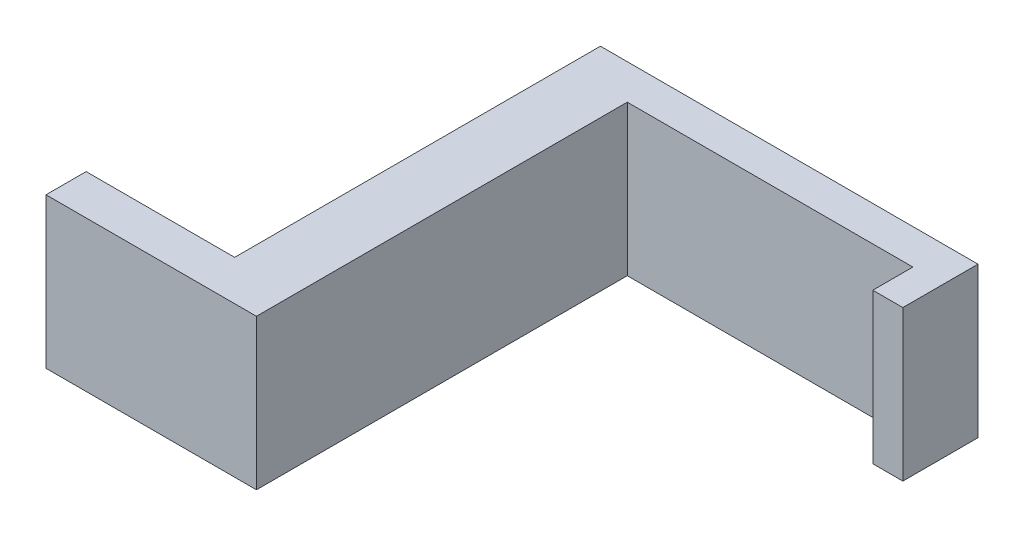
SolidWorks part; units mm, degrees
ref_plane "Front Plane" through (0, 0, 0) normal (0, 0, 1) x (1, 0, 0)
ref_plane "Top Plane" through (0, 0, 0) normal (0, 1, 0) x (1, 0, 0)
ref_plane "Right Plane" through (0, 0, 0) normal (1, 0, 0) x (0, 0, -1)
sketch "Sketch2" plane through (0, 0, 0) normal (0, 1, 0) x (1, 0, 0)
  line L0 (0, 0) -> (0, 22)
  line L1 (0, 22) -> (19, 22)
  line L2 (19, 22) -> (19, 19.3331)
  line L3 (19, 19.3331) -> (21, 19.3331)
  line L4 (21, 19.3331) -> (21, 24.3331)
  line L5 (21, 24.3331) -> (-4.1195, 24.3331)
  line L6 (-4.1195, 24.3331) -> (-4.1195, 0)
  line L7 (-4.1195, 0) -> (-14, 0)
  line L8 (-14, 0) -> (-14, -2.6706)
  line L9 (-14, -2.6706) -> (0, -2.6706)
  line L10 (0, -2.6706) -> (0, 0)
extrude "Boss-Extrude1" add sketch "Sketch2" along normal blind 10
